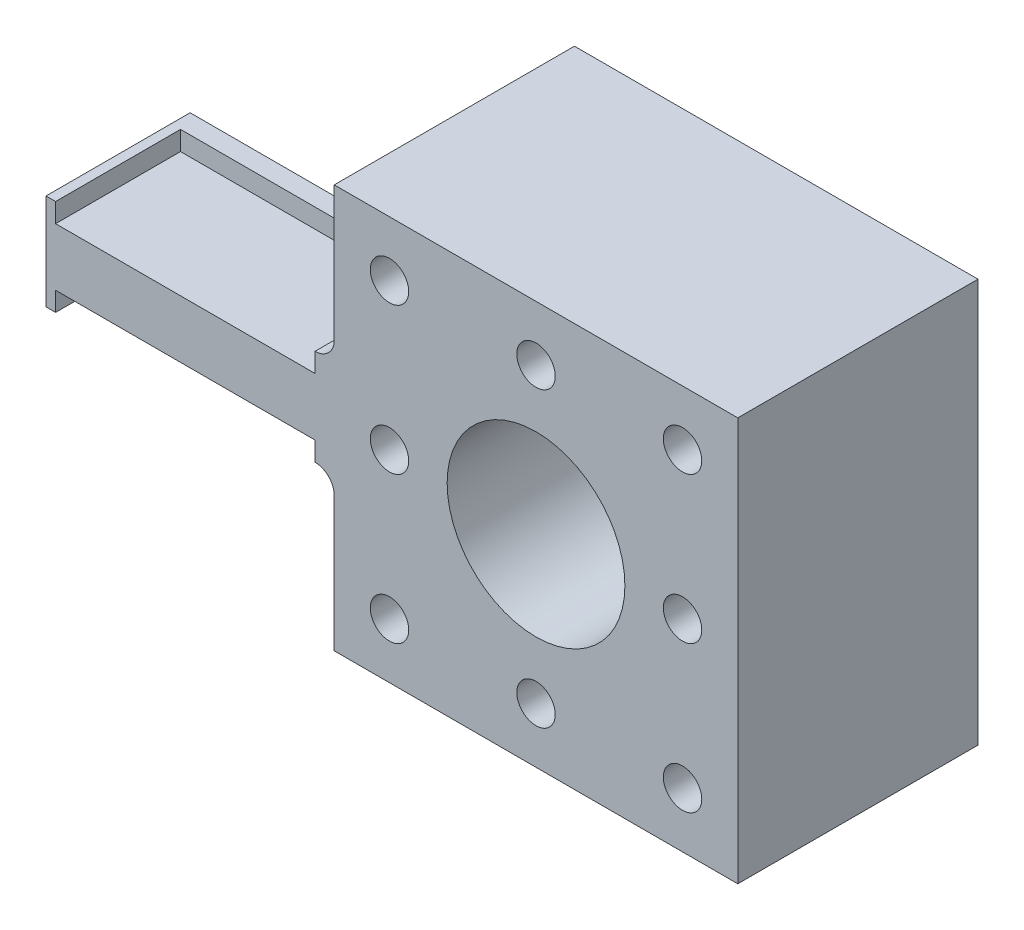
SolidWorks part; units mm, degrees
ref_plane "정면" through (0, 0, 0) normal (0, 0, 1) x (1, 0, 0)
ref_plane "윗면" through (0, 0, 0) normal (0, 1, 0) x (1, 0, 0)
ref_plane "우측면" through (0, 0, 0) normal (1, 0, 0) x (0, 0, -1)
sketch "스케치1" plane through (0, 0, 0) normal (0, 0, 1) x (1, 0, 0)
  line L1 (0, 0) -> (42, 0)
  line L2 (0, 0) -> (0, -42)
  line L3 (0, -42) -> (42, -42)
  line L4 (42, 0) -> (42, -42)
  dimension "D1" = 42
  dimension "D2" = 42
extrude "보스-돌출1" add sketch "스케치1" along normal blind 25
sketch "스케치2" plane through (0, 0, 25) normal (0, 0, 1) x (1, 0, 0)
  line L0 (42, 0) -> (0, 0) construction
  line L1 (42, -42) -> (42, 0) construction
  circle A0 centre (21, -21) radius 9.25
  dimension "D1" = 18.5
  dimension "D2" = 21
  dimension "D3" = 21
extrude "컷-돌출1" cut sketch "스케치2" against normal through all
sketch "스케치3" plane through (0, 0, 25) normal (0, 0, 1) x (1, 0, 0)
  line L4 (21, -21) -> (21, 14.351) construction
  line L5 (21, -21) -> (21, -51.5) construction
  line L6 (21, -21) -> (51.5, -21) construction
  line L7 (21, -21) -> (-19.6562, -21) construction
  circle A0 centre (36.25, -36.25) radius 2
  circle A1 centre (5.75, -36.25) radius 2
  circle A2 centre (36.25, -5.75) radius 2
  circle A3 centre (5.75, -5.75) radius 2
  circle A4 centre (36.25, -21) radius 2
  circle A5 centre (21, -5.75) radius 2
  circle A6 centre (21, -36.25) radius 2
  circle A7 centre (5.75, -21) radius 2
  dimension "D1" = 4
  dimension "D4" = 15.25
  dimension "D5" = 4
  dimension "D9" = 4
  dimension "D12" = 4
  dimension "D13" = 15.25
  dimension "D16" = 15.25
  dimension "D18" = 15.25
  dimension "D20" = 15.25
  dimension "D21" = 4
  dimension "D3" = 4
  dimension "D19" = 4
  dimension "D17" = 4
  dimension "D6" = 15.25
  dimension "D7" = 15.25
  dimension "D8" = 15.25
  dimension "D10" = 15.25
  dimension "D11" = 15.25
  dimension "D14" = 15.25
  dimension "D15" = 15.25
extrude "컷-돌출2" cut sketch "스케치3" against normal blind 3
sketch "스케치4" plane through (0, 0, 0) normal (-1, 0, 0) x (0, 0, 1)
  line L0 (25, 0) -> (25, -42) construction
  line L1 (25, -42) -> (0, -42) construction
  line L2 (25, -21) -> (25, -26)
  line L3 (25, -26) -> (10, -26)
  line L4 (10, -16) -> (10, -26)
  line L7 (10, -16) -> (25, -16)
  line L8 (25, -16) -> (25, -21)
  line L9 (25, 0) -> (0, 0) construction
  dimension "D1" = 10
  dimension "D2" = 15
  dimension "D3" = 16
  dimension "D4" = 16
extrude "보스-돌출2" add sketch "스케치4" along normal blind 30
sketch "스케치5" plane through (0, -26, 0) normal (0, -1, 0) x (-1, 0, 0)
  line L0 (30, -25) -> (0, -25) construction
  line L1 (2, -12) -> (29, -12)
  line L2 (2, -12) -> (2, -25)
  line L3 (2, -25) -> (29, -25)
  line L4 (29, -12) -> (29, -25)
  line L5 (0, -10) -> (0, -25) construction
  point P6 (8.9832, -23.3662)
  dimension "D1" = 27
  dimension "D2" = 2
  dimension "D3" = 13
extrude "컷-돌출3" cut sketch "스케치5" against normal blind 2
sketch "스케치6" plane through (0, -16, 0) normal (0, 1, 0) x (1, 0, 0)
  line L0 (-30, -25) -> (0, -25) construction
  line L1 (-29, -12) -> (-2, -12)
  line L2 (-29, -12) -> (-29, -25)
  line L3 (-29, -25) -> (-2, -25)
  line L4 (-2, -12) -> (-2, -25)
  line L6 (0, -25) -> (0, -10) construction
  dimension "D1" = 27
  dimension "D2" = 2
  dimension "D3" = 13
extrude "컷-돌출4" cut sketch "스케치6" against normal blind 2
fillet "필렛1" radius 2 2 edges at (0, -16, 17.5) (0, -26, 17.5)
